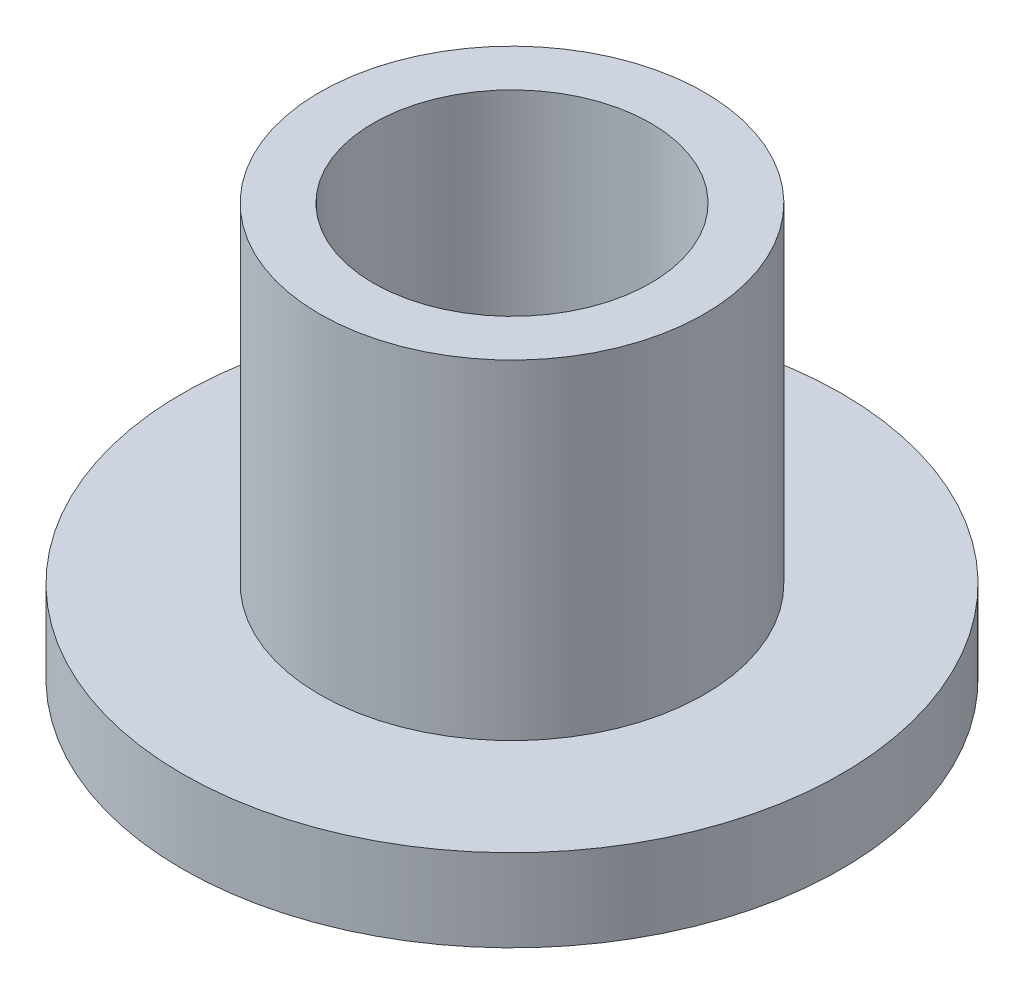
SolidWorks part; units mm, degrees
ref_plane "Plano frontal" through (0, 0, 0) normal (0, 0, 1) x (1, 0, 0)
ref_plane "Plano superior" through (0, 0, 0) normal (0, 1, 0) x (1, 0, 0)
ref_plane "Plano direito" through (0, 0, 0) normal (1, 0, 0) x (0, 0, -1)
sketch "Esboço1" plane through (0, 0, 0) normal (0, 1, 0) x (1, 0, 0)
  circle A0 centre (0, 0) radius 12
  dimension "D1" = 24
extrude "Ressalto-extrusão1" add sketch "Esboço1" along normal blind 3
sketch "Esboço2" plane through (0, 3, 0) normal (0, 1, 0) x (1, 0, 0)
  circle A0 centre (0, 0) radius 7
  dimension "D1" = 14
extrude "Ressalto-extrusão2" add sketch "Esboço2" along normal blind 12
sketch "Esboço3" plane through (0, 15, 0) normal (0, 1, 0) x (1, 0, 0)
  circle A0 centre (0, 0) radius 5.05
  dimension "D1" = 10.1
extrude "Corte-extrusão1" cut sketch "Esboço3" against normal through all
